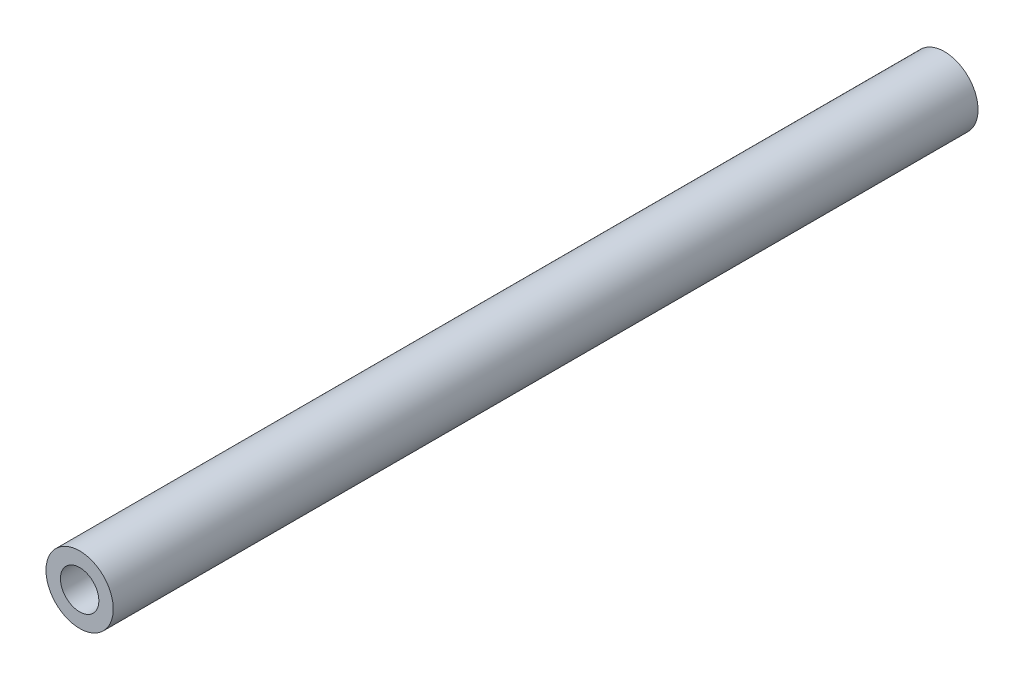
SolidWorks part; units mm, degrees
ref_plane "前视基准面" through (0, 0, 0) normal (0, 0, 1) x (1, 0, 0)
ref_plane "上视基准面" through (0, 0, 0) normal (0, 1, 0) x (1, 0, 0)
ref_plane "右视基准面" through (0, 0, 0) normal (1, 0, 0) x (0, 0, -1)
sketch "草图1" plane through (0, 0, 0) normal (0, 0, 1) x (1, 0, 0)
  circle A0 centre (0, 0) radius 1.75
  circle A1 centre (0, 0) radius 1
  dimension "D1" = 3.5
  dimension "D2" = 2
extrude "凸台-拉伸1" add sketch "草图1" along normal mid plane 45
